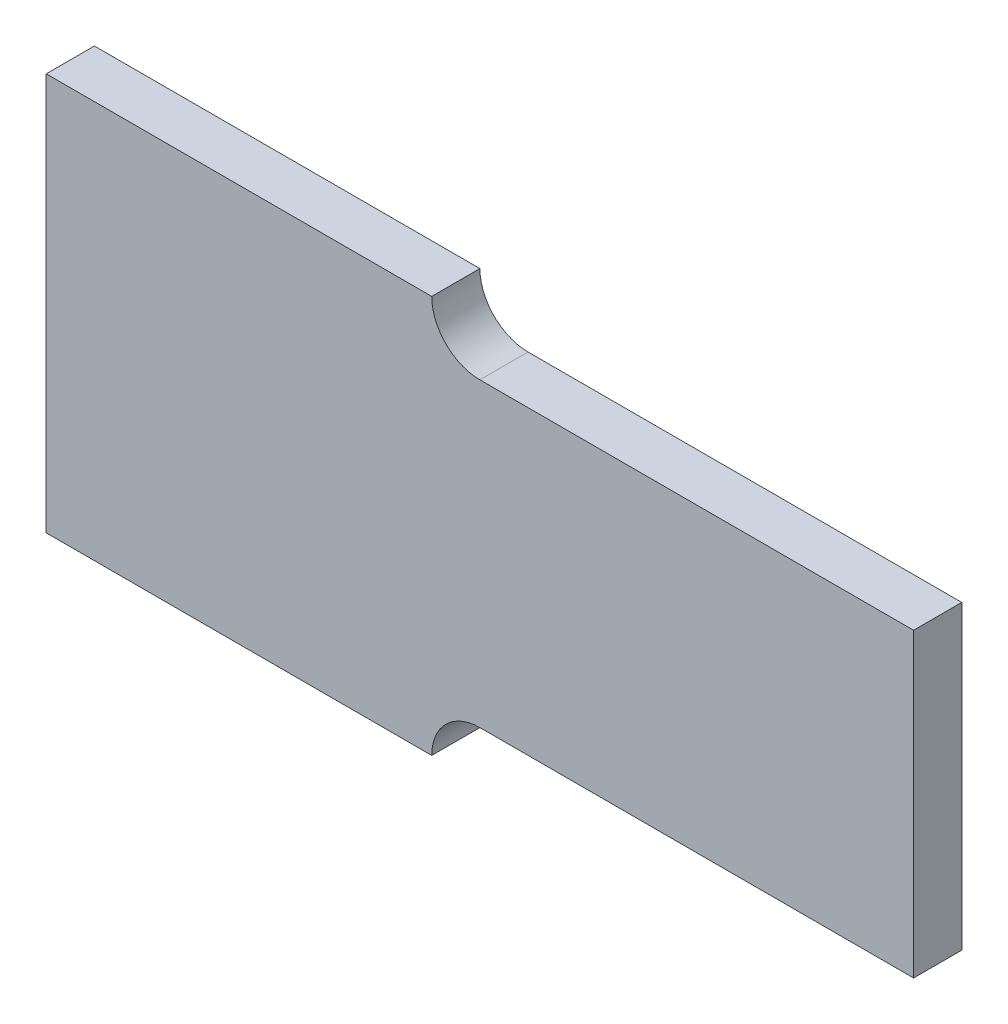
SolidWorks part; units mm, degrees
ref_plane "Front Plane" through (0, 0, 0) normal (0, 0, 1) x (1, 0, 0)
ref_plane "Top Plane" through (0, 0, 0) normal (0, 1, 0) x (1, 0, 0)
ref_plane "Right Plane" through (0, 0, 0) normal (1, 0, 0) x (0, 0, -1)
sketch "Sketch1" plane through (0, 0, 0) normal (0, 0, 1) x (1, 0, 0)
  line L0 (101.6, 104.775) -> (0, 104.775)
  line L1 (0, 104.775) -> (0, 0)
  line L2 (0, 0) -> (101.6, 0)
  line L4 (114.3, 12.7) -> (228.6, 12.7)
  line L5 (228.6, 12.7) -> (228.6, 92.075)
  line L6 (228.6, 92.075) -> (114.3, 92.075)
  arc A0 (101.6, 104.775) -> (114.3, 92.075) centre (114.3, 104.775) ccw
  arc A1 (114.3, 12.7) -> (101.6, 0) centre (114.3, 0) ccw
  dimension "D1" = 12.7
  dimension "D2" = 12.7
  dimension "D3" = 79.375
  dimension "D4" = 104.775
  dimension "D5" = 228.6
  dimension "D6" = 12.7
  dimension "D7" = 114.3
extrude "Boss-Extrude1" add sketch "Sketch1" along normal blind 12.7
